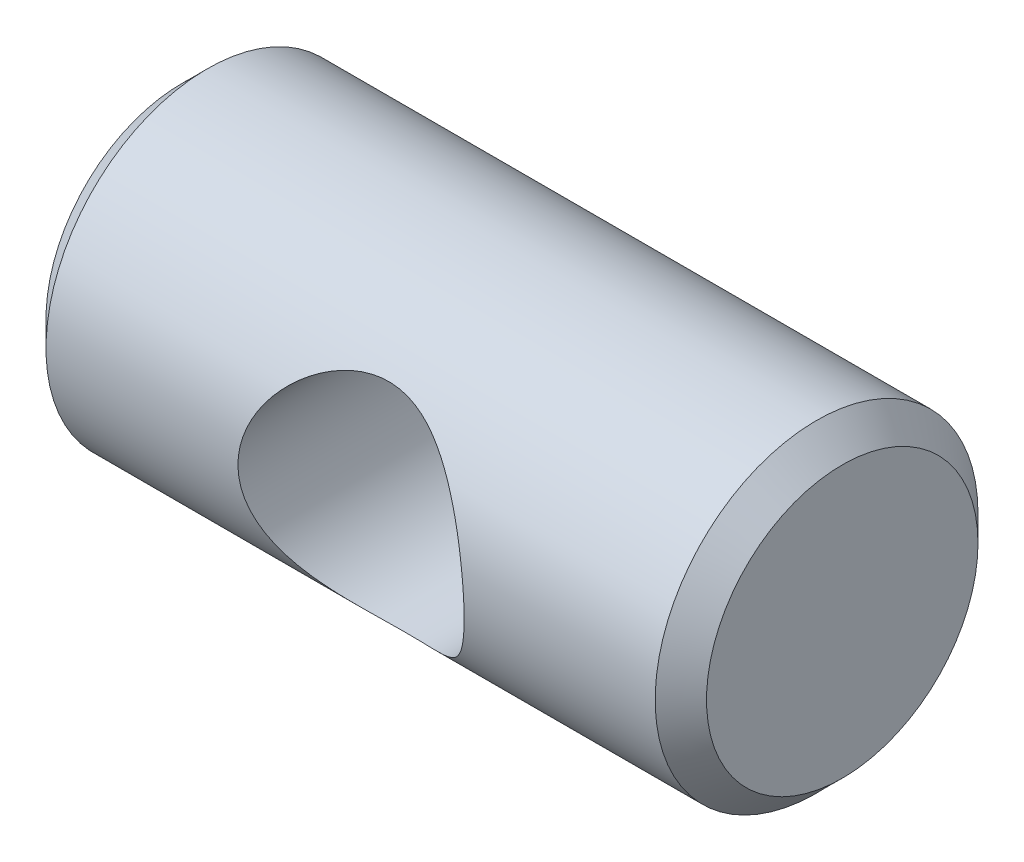
SolidWorks part; units mm, degrees
ref_plane "Front Plane" through (0, 0, 0) normal (0, 0, 1) x (1, 0, 0)
ref_plane "Top Plane" through (0, 0, 0) normal (0, 1, 0) x (1, 0, 0)
ref_plane "Right Plane" through (0, 0, 0) normal (1, 0, 0) x (0, 0, -1)
sketch "Sketch1" plane through (0, 0, 0) normal (1, 0, 0) x (0, 0, -1)
  circle A0 centre (0, 0) radius 4.78
  dimension "D1" = 9.56
extrude "Boss-Extrude1" add sketch "Sketch1" along normal mid plane 19.56
sketch "Sketch3" plane through (0, 0, 0) normal (0, 0, 1) x (1, 0, 0)
  line L0 (-4.0247, -0.25) -> (4.3999, -0.25) construction
  line L1 (9.78, 0) -> (-9.78, 0) construction
  circle A0 centre (0, -0.25) radius 3.34
  dimension "D1" = 6.68
  dimension "D2" = 0.25
extrude "Cut-Extrude1" cut sketch "Sketch3" against normal through all both and the other way through all
chamfer "Chamfer1" distance 0.76 angle 45 2 edges at (9.78, 0, -4.78) (-9.78, 0, -4.78)
